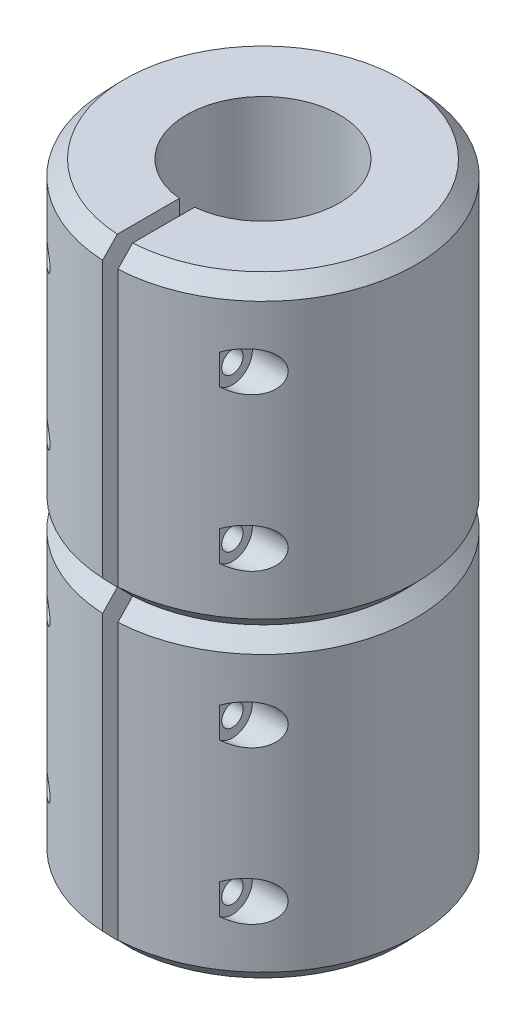
SolidWorks part; units mm, degrees
ref_plane "Front Plane" through (0, 0, 0) normal (0, 0, 1) x (1, 0, 0)
ref_plane "Top Plane" through (0, 0, 0) normal (0, 1, 0) x (1, 0, 0)
ref_plane "Right Plane" through (0, 0, 0) normal (1, 0, 0) x (0, 0, -1)
sketch "Sketch5" plane through (0, 0, 0) normal (0, 0, 1) x (1, 0, 0)
  line L0 (0, -53.1915) -> (0, 53.1915) construction
  line L1 (-56.4539, 0) -> (56.4539, 0) construction
  line L2 (-9.0412, 20) -> (0, 20)
  line L3 (-9.0412, 20) -> (-10, 19)
  line L4 (-10, 19) -> (-10, 1)
  line L5 (-10, 1) -> (-9.0412, 0)
  line L6 (-10, -1) -> (-9.0412, 0)
  line L7 (0, 20) -> (0, -20)
  line L8 (-10, -19) -> (-10, -1)
  line L9 (-9.0412, -20) -> (-10, -19)
  line L10 (-9.0412, -20) -> (0, -20)
  point P4 (0, 0)
  point P8 (0, 0)
  dimension "D1" = 9.0412
  dimension "D2" = 10
  dimension "D3" = 1
  dimension "D4" = 1
  dimension "D5" = 9.0412
revolve "Revolve2" add sketch "Sketch5" angle 360 about L0
sketch "Sketch6" plane through (0, -20, 0) normal (0, -1, 0) x (-1, 0, 0)
  line L1 (-3, 4) -> (-3, -4)
  line L3 (3, 4) -> (3, -4)
  line L5 (-1.9886, 4.5875) -> (1.9886, -4.5875) construction
  line L6 (1.9886, 4.5875) -> (-1.9886, -4.5875) construction
  arc A0 (3, 4) -> (-3, 4) centre (0, 0) ccw
  arc A1 (-3, -4) -> (3, -4) centre (0, 0) ccw
extrude "Cut-Extrude2" cut sketch "Sketch6" against normal blind 20
sketch "Sketch8" plane through (0, 20, 0) normal (0, 1, 0) x (1, 0, 0)
  circle A0 centre (0, 0) radius 5
extrude "Cut-Extrude3" cut sketch "Sketch8" against normal blind 20
sketch "Sketch9" plane through (0, 20, 0) normal (0, 1, 0) x (1, 0, 0)
  line L0 (0, -5) -> (0, -10.4158) construction
  line L1 (-0.5, -4.9749) -> (-0.5, -10.4038)
  line L2 (0.5, -4.9749) -> (0.5, -10.4038)
  line L3 (0.5, 0) -> (0.5, -11.9227) construction
  line L4 (0, 0) -> (0, -11.9227) construction
  line L5 (-0.5, 0) -> (-0.5, -11.9227) construction
  arc A0 (-0.5, -4.9749) -> (0.5, -4.9749) centre (0, 0) ccw
  arc A1 (-0.5, -10.4038) -> (0.5, -10.4038) centre (0, 0) ccw
  point P4 (0, 0)
  point P9 (0, 0)
  dimension "D1" = 0.5
  dimension "D2" = 0.5
extrude "Cut-Extrude4" cut sketch "Sketch9" against normal through all both and the other way through all contours L1 A1 L2 A0
ref_plane "Plane2" through (9.5, 0, 0) normal (1, 0, 0) x (0, 0, -1)
sketch "Sketch11" plane through (9.5, 0, 0) normal (1, 0, 0) x (0, 0, -1)
  line L0 (-19.788, 0) -> (19.788, 0) construction
  line L1 (-4.9749, 20) -> (-9.0274, 20) construction
  circle A0 centre (-7.5, 15) radius 0.7
  circle A1 centre (-7.5, 5) radius 0.7
  circle A2 centre (-7.5, -5) radius 0.7
  circle A3 centre (-7.5, -15) radius 0.7
  point P6 (0, 0)
  point P11 (0, 0)
  dimension "D1" = 1.4
  dimension "D2" = 1.4
  dimension "D3" = 5
  dimension "D4" = 5
extrude "Cut-Extrude5" cut sketch "Sketch11" against normal through all
sketch "Sketch13" plane through (9.5, 0, 0) normal (1, 0, 0) x (0, 0, -1)
  circle A0 centre (-7.5, 15) radius 1.3
  circle A1 centre (-7.5, 5) radius 1.3
  circle A2 centre (-7.5, -5) radius 1.3
  circle A3 centre (-7.5, -15) radius 1.3
extrude "Cut-Extrude6" cut sketch "Sketch13" against normal blind 4
